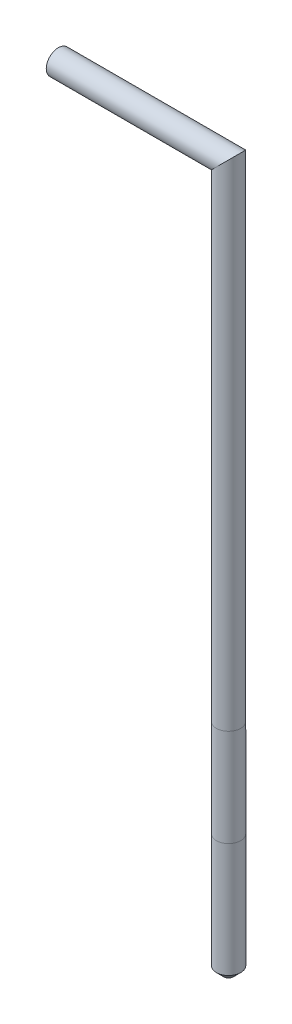
SolidWorks part; units mm, degrees
material "AISI 1020"
ref_plane "Спереди" through (0, 0, 0) normal (0, 0, 1) x (1, 0, 0)
ref_plane "Сверху" through (0, 0, 0) normal (0, 1, 0) x (1, 0, 0)
ref_plane "Справа" through (0, 0, 0) normal (1, 0, 0) x (0, 0, -1)
sketch "Эскиз1" plane through (0, 0, 0) normal (0, 0, 1) x (1, 0, 0)
  line L0 (0, 0) -> (0, 40)
  line L1 (10, 40) -> (-10, 40) construction
  line L2 (0, 40) -> (0, 240)
  line L3 (0, 240) -> (-70, 240)
  line L4 (0, 0) -> (0, -50)
  line L5 (-482.5, 0) -> (512.5, 0) construction
  line L6 (6, 230) -> (-6, 230) construction
  dimension "D1" = 50
  dimension "D2" = 10
  dimension "D3" = 70
ref_plane "Плоскость1" through (0, -50, 0) normal (0, 1, 0) x (1, 0, 0)
sketch "Эскиз2" plane through (0, -50, 0) normal (0, 1, 0) x (1, 0, 0)
  circle A0 centre (0, 0) radius 5
  dimension "D1" = 10
sweep "По траектории1" add profiles "Эскиз2" path "Эскиз1"
chamfer "Фаска1" distance 3 angle 45
